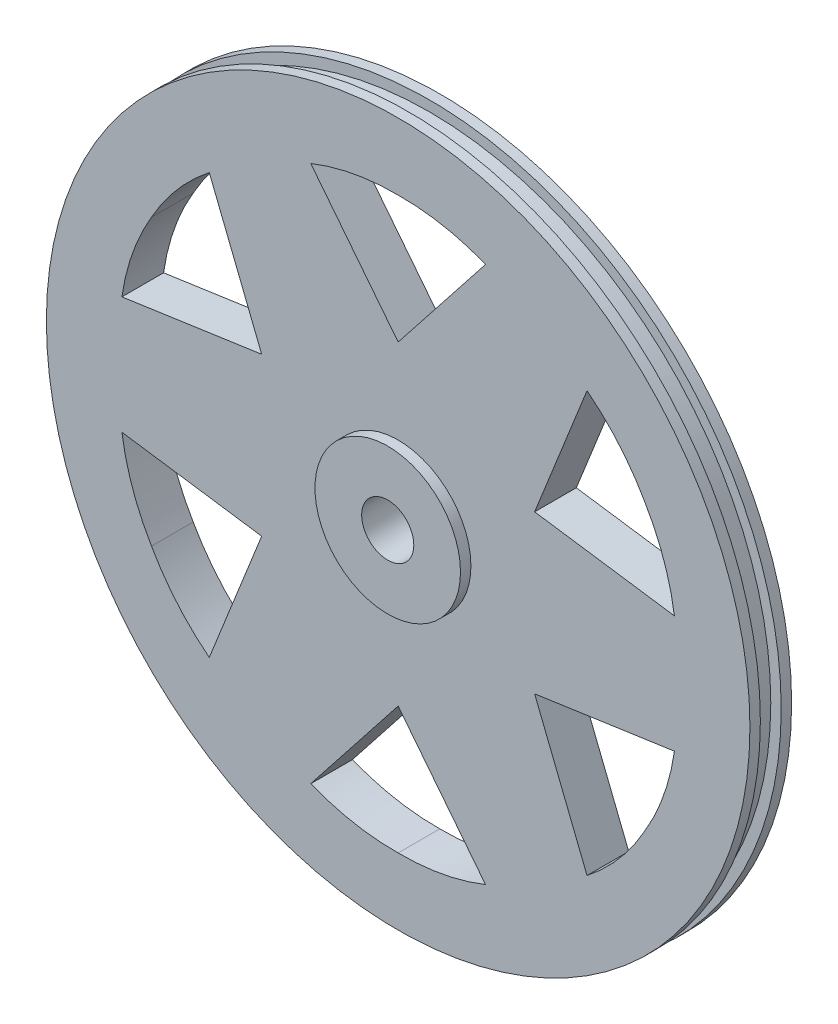
SolidWorks part; units mm, degrees
ref_plane "Front Plane" through (0, 0, 0) normal (0, 0, 1) x (1, 0, 0)
ref_plane "Top Plane" through (0, 0, 0) normal (0, 1, 0) x (1, 0, 0)
ref_plane "Right Plane" through (0, 0, 0) normal (1, 0, 0) x (0, 0, -1)
sketch "Sketch1" plane through (0, 0, 0) normal (0, 0, 1) x (1, 0, 0)
  circle A0 centre (0, 0) radius 67.5
  circle A1 centre (0, 0) radius 5
  dimension "D1" = 135
  dimension "D2" = 10
extrude "Boss-Extrude1" add sketch "Sketch1" along normal mid plane 8
sketch "Sketch2" plane through (0, 0, 0) normal (0, 0, 1) x (1, 0, 0)
  line L0 (0, 0) -> (0, 52.9264) construction
  line L1 (0, 30.2392) -> (-16.7682, 51.5291)
  line L2 (0, 30.2392) -> (16.7682, 51.5291)
  arc A0 (-16.7682, 51.5291) -> (0, 54.653) centre (-0.5568, 11.0765) cw
  arc A1 (16.7682, 51.5291) -> (0, 54.653) centre (0.5568, 11.0765) ccw
  point P9 (0, 30.9635)
  point P10 (-12.48, 47.8487)
  point P11 (-20.5363, 49.6451)
  point P12 (-0.5568, 25.5291)
  point P13 (-16.7682, 51.5291)
  point P14 (-0.5568, 30.2392)
extrude "Cut-Extrude1" cut sketch "Sketch2" along normal mid plane 8
pattern_circular "CirPattern1" count 6 over 360 about axis through (0, 0, 0) along (0, 0, 1) of "Cut-Extrude1"
sketch "Sketch3" plane through (0, 0, 0) normal (0, 0, 1) x (1, 0, 0)
  circle A0 centre (0, 0) radius 67.5
  circle A1 centre (0, 0) radius 65.5
  circle A2 centre (0, 0) radius 67.5 construction
  dimension "D1" = 0
  dimension "D2" = 2
extrude "Cut-Extrude2" cut sketch "Sketch3" against normal mid plane 4
sketch "Sketch4" plane through (0, 0, 4) normal (0, 0, 1) x (1, 0, 0)
  circle A0 centre (0, 0) radius 13.9624
  circle A1 centre (0, 0) radius 5
extrude "Boss-Extrude2" add sketch "Sketch4" along normal blind 2
